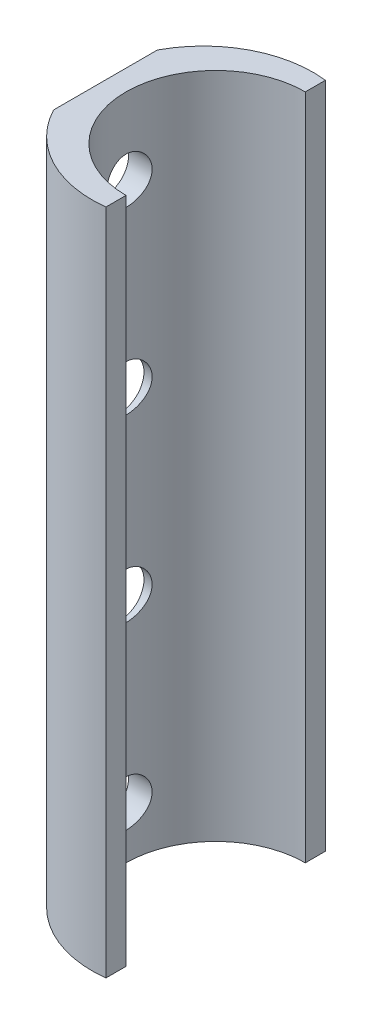
SolidWorks part; units mm, degrees
ref_plane "Front Plane" through (0, 0, 0) normal (0, 0, 1) x (1, 0, 0)
ref_plane "Top Plane" through (0, 0, 0) normal (0, 1, 0) x (1, 0, 0)
ref_plane "Right Plane" through (0, 0, 0) normal (1, 0, 0) x (0, 0, -1)
sketch "Sketch1" plane through (0, 0, 0) normal (0, 0, 1) x (1, 0, 0)
  line L8 (-76.5804, 84.1602) -> (-76.5804, 48.2602)
  line L9 (-76.5804, 48.2602) -> (-73.5804, 48.2602)
  line L10 (-73.5804, 48.2602) -> (-73.5804, -9.9398)
  line L11 (-73.5804, -9.9398) -> (-76.5804, -9.9398)
  line L12 (-76.5804, -9.9398) -> (-76.5804, -45.8398)
  line L16 (-76.5804, 84.1602) -> (-72.5804, 84.1602)
  line L17 (-72.5804, 84.1602) -> (-72.5804, -45.8398)
  line L18 (-72.5804, -45.8398) -> (-76.5804, -45.8398)
  dimension "D6" = 35.9
  dimension "D7" = 4
  dimension "D8" = 3
  dimension "D9" = 58.2
  dimension "D10" = 35.9
  dimension "D11" = 130
  dimension "D12" = 3
  dimension "D13" = 4
  dimension "D14" = 1
extrude "Boss-Extrude1" add sketch "Sketch1" along normal blind 20.2
sketch "Sketch2" plane through (0, 84.1602, 0) normal (0, 1, 0) x (1, 0, 0)
  line L2 (-72.5804, 0) -> (-69.3627, 0)
  line L3 (-72.5804, -20.2) -> (-69.3627, -20.2)
  line L4 (-55.1204, -10.1) -> (-55.1204, 7.36) construction
  line L5 (-55.1204, 7.36) -> (-55.1204, 11.27) construction
  line L6 (-55.1204, -27.56) -> (-55.1204, -31.47) construction
  line L7 (-55.1204, 11.27) -> (-55.1204, 7.36)
  line L8 (-55.1204, -27.56) -> (-55.1204, -31.47)
  line L9 (-76.5804, 0) -> (-69.3627, 0)
  circle A0 centre (-55.1204, -10.1) radius 17.46
  arc A1 (-76.5804, 0) -> (-55.1204, 11.27) centre (-57.667, -9.9477) cw
  arc A2 (-76.5804, -20.2) -> (-55.1204, -31.47) centre (-57.667, -10.2523) ccw
  point P0 (0, 0)
  dimension "D4" = 3.91
  dimension "D2" = 3.2178
  dimension "D3" = 3.91
extrude "Boss-Extrude3" add sketch "Sketch2" against normal blind 130
sketch "Sketch7" plane through (-76.5804, 0, 0) normal (-1, 0, 0) x (0, 0, 1)
  line L0 (10.1, 84.1602) -> (10.1, 69.1602) construction
  line L1 (20.2, 84.1602) -> (0, 84.1602) construction
  line L2 (10.1, 69.1602) -> (10.1, 34.1602) construction
  line L3 (10.1, 34.1602) -> (10.1, -0.8398) construction
  line L4 (10.1, -0.8398) -> (10.1, 34.1602) construction
  line L5 (10.1, -0.8398) -> (10.1, -35.8398) construction
  circle A0 centre (10.1, 69.1602) radius 4.5
  circle A1 centre (10.1, 34.1602) radius 4.5
  circle A2 centre (10.1, -0.8398) radius 4.5
  circle A3 centre (10.1, -35.8398) radius 4.5
  dimension "D6" = 9
  dimension "D7" = 9
  dimension "D8" = 9
  dimension "D9" = 9
  dimension "D1" = 15
  dimension "D2" = 35
  dimension "D3" = 35
  dimension "D4" = 35
  dimension "D5" = 35
extrude "Cut-Extrude1" cut sketch "Sketch7" against normal blind 10
sketch "Sketch8" plane through (0, 0, 0) normal (0, 0, 1) x (1, 0, 0)
  line L1 (-73.5804, 48.2602) -> (-76.5804, 48.2602)
  line L2 (-73.5804, 48.2602) -> (-73.5804, -9.9398)
  line L3 (-73.5804, -9.9398) -> (-76.5804, -9.9398)
  line L4 (-76.5804, 48.2602) -> (-76.5804, -9.9398)
extrude "Cut-Extrude2" cut sketch "Sketch8" against normal through all both and the other way through all
